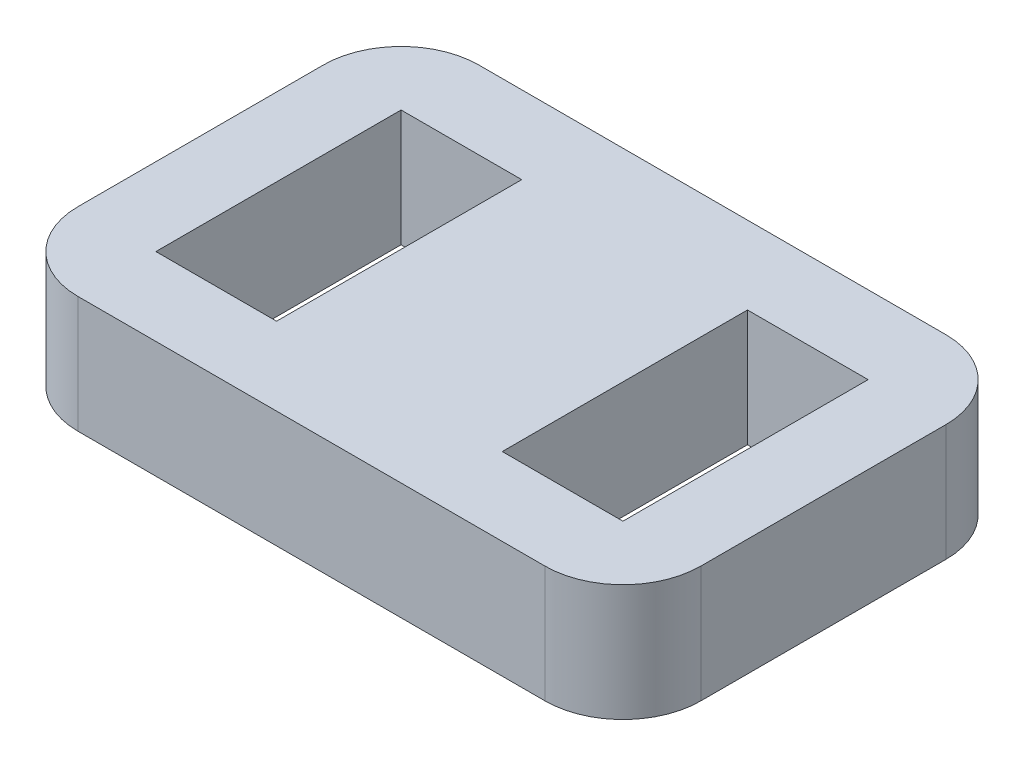
SolidWorks part; units mm, degrees
ref_plane "Front Plane" through (0, 0, 0) normal (0, 0, 1) x (1, 0, 0)
ref_plane "Top Plane" through (0, 0, 0) normal (0, 1, 0) x (1, 0, 0)
ref_plane "Right Plane" through (0, 0, 0) normal (1, 0, 0) x (0, 0, -1)
sketch "Sketch1" plane through (0, 0, 0) normal (0, 1, 0) x (1, 0, 0)
  line L0 (-8, 3.15) -> (-8, -3.15)
  line L1 (-6, -5.15) -> (-2.9, -5.15)
  line L5 (-2.9, -5.15) -> (6, -5.15)
  line L6 (8, -3.15) -> (8, 3.15)
  line L7 (8, 0) -> (-8, 0) construction
  line L8 (-2.9, 5.15) -> (6, 5.15)
  line L12 (-6, 5.15) -> (-2.9, 5.15)
  line L13 (0, 0) -> (0, 6.0904) construction
  line L14 (-6, 3.15) -> (-2.9, 3.15)
  line L15 (-6, 3.15) -> (-6, -3.15)
  line L16 (-6, -3.15) -> (-2.9, -3.15)
  line L17 (-2.9, 3.15) -> (-2.9, -3.15)
  line L18 (-6, 3.15) -> (-2.9, -3.15) construction
  line L19 (-6, -3.15) -> (-2.9, 3.15) construction
  line L20 (6, -3.15) -> (2.9, -3.15)
  line L21 (2.9, 3.15) -> (2.9, -3.15)
  line L22 (6, 3.15) -> (2.9, 3.15)
  line L23 (6, 3.15) -> (6, -3.15)
  arc A0 (-8, -3.15) -> (-6, -5.15) centre (-6, -3.15) ccw
  arc A1 (6, -5.15) -> (8, -3.15) centre (6, -3.15) ccw
  arc A2 (6, 5.15) -> (8, 3.15) centre (6, 3.15) cw
  arc A3 (-6, 5.15) -> (-8, 3.15) centre (-6, 3.15) ccw
  point P6 (-8, -5.15)
  point P12 (8, -5.15)
  point P15 (-4.45, 0)
  point P21 (-4.45, 5.15)
  point P29 (8, 5.15)
  point P32 (-8, 5.15)
  dimension "D6" = 2
  dimension "D1" = 6.3
  dimension "D2" = 3.1
  dimension "D3" = 5.8
  dimension "D4" = 2
  dimension "D5" = 2
extrude "Boss-Extrude1" add sketch "Sketch1" along normal blind 3
